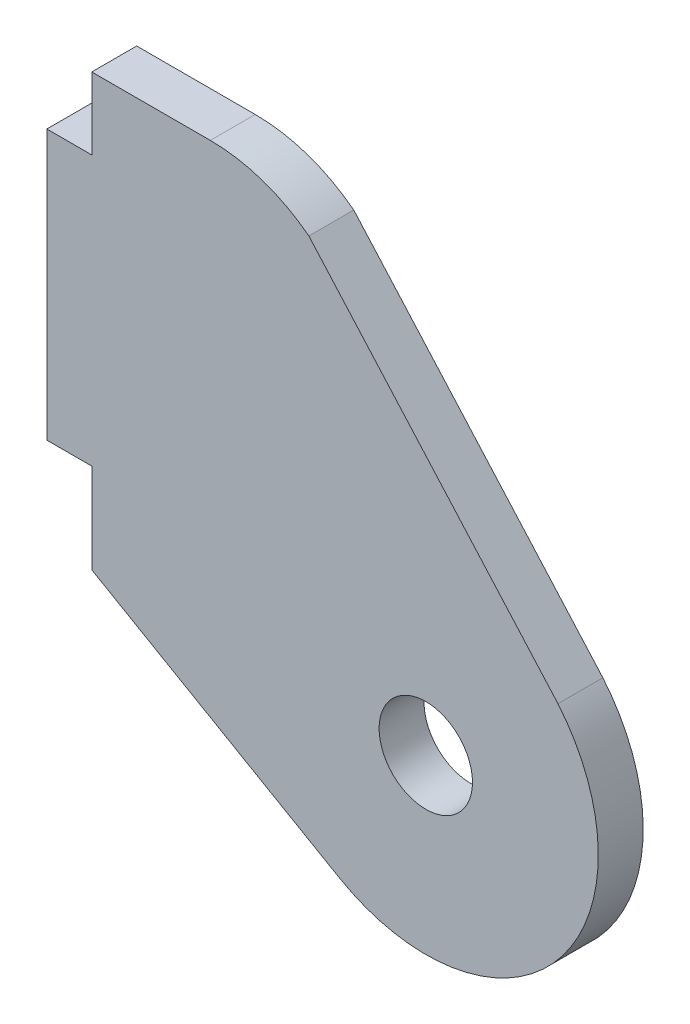
SolidWorks part; units mm, degrees
material "AISI 4130 Steel, annealed at 865C"
ref_plane "X-Y Datum" through (0, 0, 0) normal (0, 0, 1) x (1, 0, 0)
ref_plane "X-Z Datum" through (0, 0, 0) normal (0, 1, 0) x (1, 0, 0)
ref_plane "Y-Z Datum" through (0, 0, 0) normal (1, 0, 0) x (0, 0, -1)
sketch "Sketch1" plane through (0, 0, 0) normal (0, 0, 1) x (1, 0, 0)
  line L8 (-79.4095, -48.8706) -> (-79.4095, -29.8206)
  line L9 (-79.4095, -29.8206) -> (-76.2345, -29.8206)
  line L10 (-76.2345, -29.8206) -> (-76.2345, -24.7406)
  line L11 (-76.2345, -24.7406) -> (-67.8525, -24.7406)
  line L12 (-79.4095, -48.8706) -> (-76.2345, -48.8706)
  line L13 (-76.2345, -48.8706) -> (-76.2345, -55.2206)
  line L14 (-76.2345, -55.2206) -> (-58.7169, -65.3344)
  line L18 (-60.8897, -27.1062) -> (-43.2813, -46.9389)
  arc A2 (-58.7169, -65.3344) -> (-43.2813, -46.9389) centre (-52.6209, -54.7758) ccw
  circle A4 centre (-52.6209, -54.7758) radius 3.3
  arc A5 (-67.8525, -24.7406) -> (-60.8897, -27.1062) centre (-67.8525, -36.1706) cw
  dimension "D6" = 6.6
  dimension "D7" = 12.192
  dimension "D9" = 11.43
  dimension "D1" = 19.05
  dimension "D2" = 5.08
  dimension "D3" = 6.35
  dimension "D4" = 120
  dimension "D5" = 26.7886
  dimension "D8" = 8.382
  dimension "D10" = 37.53
  dimension "D11" = 3.175
  dimension "D12" = 3.175
extrude "Boss-Extrude1" add sketch "Sketch1" along normal blind 3.175
